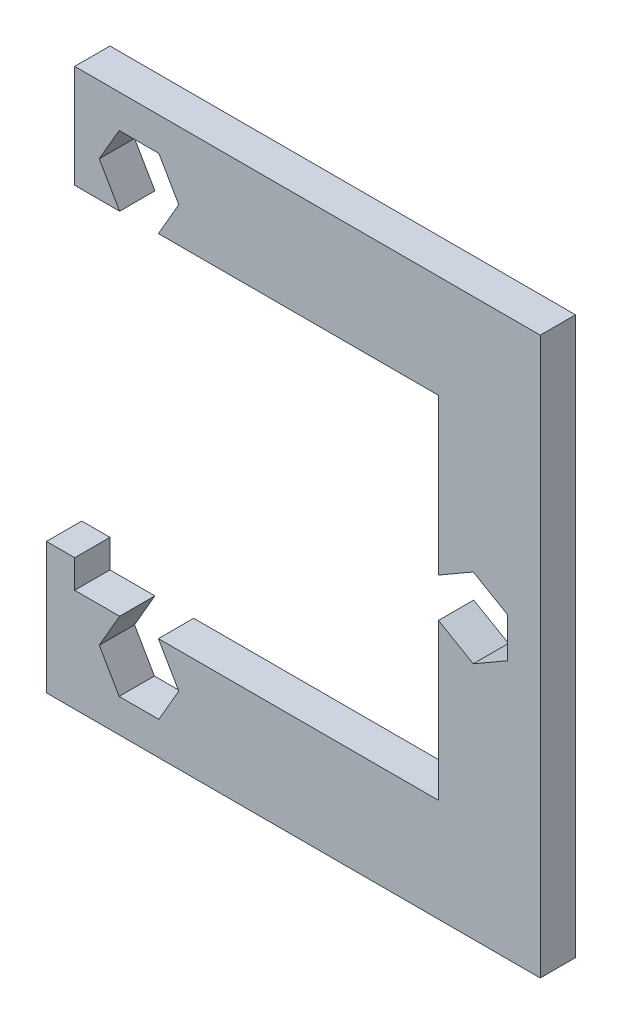
SolidWorks part; units mm, degrees
ref_plane "Front Plane" through (0, 0, 0) normal (0, 0, 1) x (1, 0, 0)
ref_plane "Top Plane" through (0, 0, 0) normal (0, 1, 0) x (1, 0, 0)
ref_plane "Right Plane" through (0, 0, 0) normal (1, 0, 0) x (0, 0, -1)
sketch "Sketch1" plane through (0, 0, 0) normal (0, 0, 1) x (1, 0, 0)
  line L0 (7421.358, 3420.4566) -> (7421.358, 3429.7276)
  line L1 (7418.818, 3379.6134) -> (7418.818, 3391.4244)
  line L2 (7421.358, 3420.4566) -> (7425.4041, 3420.4566)
  line L3 (7428.8943, 3420.4566) -> (7454.0986, 3420.4566)
  line L4 (7421.358, 3429.7276) -> (7463.268, 3429.7276)
  line L5 (7454.0986, 3420.4566) -> (7454.0986, 3406.4377)
  line L6 (7454.0986, 3402.9034) -> (7454.0986, 3388.8844)
  line L7 (7463.268, 3429.7276) -> (7463.268, 3379.6134)
  line L8 (7454.0986, 3388.8844) -> (7428.8943, 3388.8844)
  line L9 (7425.4041, 3388.8844) -> (7421.358, 3388.8844)
  line L10 (7418.818, 3379.6134) -> (7463.268, 3379.6134)
  line L11 (7454.0986, 3402.9034) -> (7457.2354, 3401.0924)
  line L12 (7457.2354, 3401.0924) -> (7460.3342, 3402.8814)
  line L13 (7460.3342, 3402.8814) -> (7460.3342, 3406.4596)
  line L14 (7460.3342, 3406.4596) -> (7457.2354, 3408.2487)
  line L15 (7457.2354, 3408.2487) -> (7454.0986, 3406.4377)
  line L16 (7428.8943, 3420.4566) -> (7430.7274, 3423.6316)
  line L17 (7430.7274, 3423.6316) -> (7428.9383, 3426.7304)
  line L18 (7428.9383, 3426.7304) -> (7425.3601, 3426.7304)
  line L19 (7425.3601, 3426.7304) -> (7423.571, 3423.6316)
  line L20 (7423.571, 3423.6316) -> (7425.4041, 3420.4566)
  line L21 (7425.4041, 3388.8844) -> (7423.571, 3385.7094)
  line L22 (7423.571, 3385.7094) -> (7425.3601, 3382.6106)
  line L23 (7425.3601, 3382.6106) -> (7428.9383, 3382.6106)
  line L24 (7428.9383, 3382.6106) -> (7430.7274, 3385.7094)
  line L25 (7430.7274, 3385.7094) -> (7428.8943, 3388.8844)
  line L26 (7421.358, 3391.4244) -> (7418.818, 3391.4244)
  line L27 (7421.358, 3391.4244) -> (7421.358, 3388.8844)
extrude "Boss-Extrude1" add sketch "Sketch1" along normal blind 3.175
